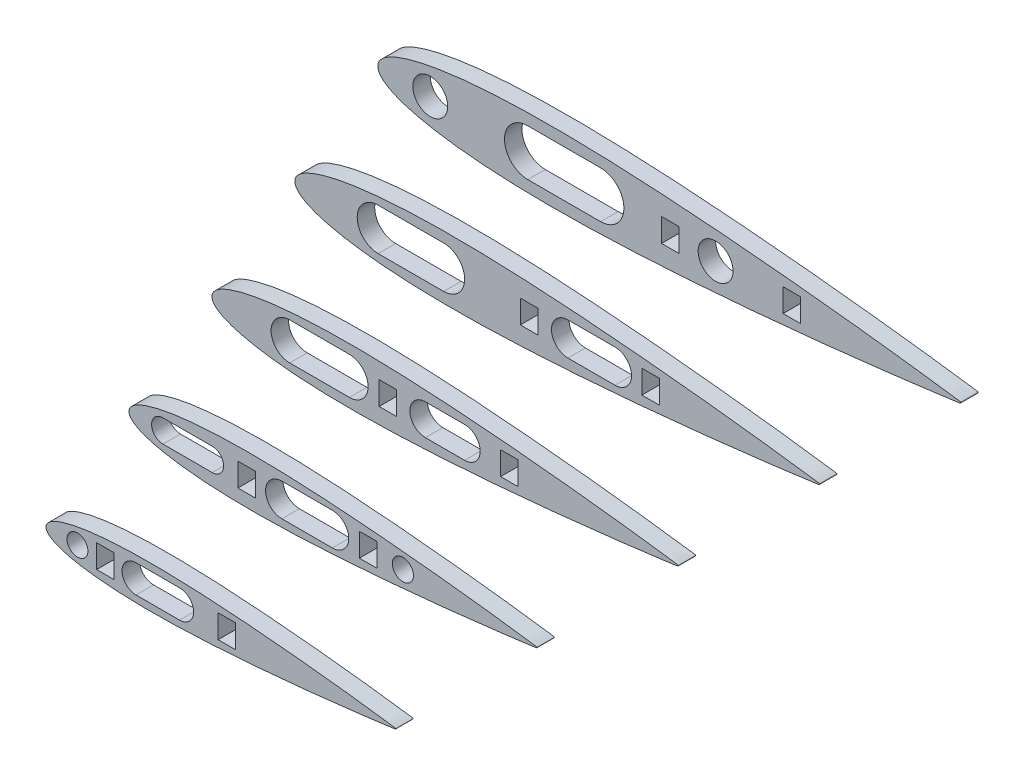
SolidWorks part; units mm, degrees
material "Balsa"
ref_plane "Front Plane" through (0, 0, 0) normal (1, 0, 0) x (0, 1, 0)
ref_plane "Top Plane" through (0, 0, 0) normal (0, 0, 1) x (0, 1, 0)
ref_plane "Right Plane" through (0, 0, 0) normal (0, 1, 0) x (-1, 0, 0)
curve "Curve1"
  spline degree 3 poles (0.0004, -0.0044, 0) (-0.0002, 0, 0) (0.0004, 0.0044, 0) (0.0023, 0.0087, 0) (0.0053, 0.0128, 0) (0.0094, 0.0167, 0) (0.0147, 0.0206, 0) (0.0211, 0.0243, 0) (0.0286, 0.0279, 0) (0.0372, 0.0313, 0) (0.0468, 0.0347, 0) (0.0576, 0.0378, 0) (0.0693, 0.0408, 0) (0.0821, 0.0436, 0) (0.0958, 0.0462, 0) (0.1104, 0.0486, 0) (0.126, 0.0507, 0) (0.1425, 0.0527, 0) (0.1597, 0.0544, 0) (0.1778, 0.056, 0) (0.1966, 0.0572, 0) (0.2162, 0.0583, 0) (0.2364, 0.0591, 0) (0.2572, 0.0596, 0) (0.2786, 0.06, 0) (0.3005, 0.0601, 0) (0.3228, 0.0599, 0) (0.3456, 0.0596, 0) (0.3688, 0.0591, 0) (0.3922, 0.0583, 0) (0.4159, 0.0574, 0) (0.4398, 0.0563, 0) (0.4638, 0.0551, 0) (0.4879, 0.0537, 0) (0.5121, 0.0522, 0) (0.5362, 0.0505, 0) (0.5602, 0.0488, 0) (0.5841, 0.0469, 0) (0.6078, 0.045, 0) (0.6313, 0.043, 0) (0.6544, 0.0409, 0) (0.6772, 0.0388, 0) (0.6995, 0.0367, 0) (0.7214, 0.0345, 0) (0.7428, 0.0324, 0) (0.7636, 0.0302, 0) (0.7838, 0.028, 0) (0.8033, 0.0259, 0) (0.8222, 0.0238, 0) (0.8402, 0.0217, 0) (0.8575, 0.0196, 0) (0.874, 0.0177, 0) (0.8895, 0.0158, 0) (0.9042, 0.014, 0) (0.9179, 0.0122, 0) (0.9307, 0.0106, 0) (0.9424, 0.0091, 0) (0.9531, 0.0077, 0) (0.9627, 0.0064, 0) (0.9713, 0.0052, 0) (0.9788, 0.0042, 0) (0.9851, 0.0033, 0) (0.9903, 0.0026, 0) (0.9944, 0.002, 0) (0.9973, 0.0017, 0) (0.999, 0.0013, 0) (1.0007, 0.0014, 0) (1.0007, -0.0014, 0) (0.999, -0.0013, 0) (0.9973, -0.0017, 0) (0.9944, -0.002, 0) (0.9903, -0.0026, 0) (0.9851, -0.0033, 0) (0.9788, -0.0042, 0) (0.9713, -0.0052, 0) (0.9627, -0.0064, 0) (0.9531, -0.0077, 0) (0.9424, -0.0091, 0) (0.9307, -0.0106, 0) (0.9179, -0.0122, 0) (0.9042, -0.014, 0) (0.8895, -0.0158, 0) (0.874, -0.0177, 0) (0.8575, -0.0196, 0) (0.8402, -0.0217, 0) (0.8222, -0.0238, 0) (0.8033, -0.0259, 0) (0.7838, -0.028, 0) (0.7636, -0.0302, 0) (0.7428, -0.0324, 0) (0.7214, -0.0345, 0) (0.6995, -0.0367, 0) (0.6772, -0.0388, 0) (0.6544, -0.0409, 0) (0.6313, -0.043, 0) (0.6078, -0.045, 0) (0.5841, -0.0469, 0) (0.5602, -0.0488, 0) (0.5362, -0.0505, 0) (0.5121, -0.0522, 0) (0.4879, -0.0537, 0) (0.4638, -0.0551, 0) (0.4398, -0.0563, 0) (0.4159, -0.0574, 0) (0.3922, -0.0583, 0) (0.3688, -0.0591, 0) (0.3456, -0.0596, 0) (0.3228, -0.0599, 0) (0.3005, -0.0601, 0) (0.2786, -0.06, 0) (0.2572, -0.0596, 0) (0.2364, -0.0591, 0) (0.2162, -0.0583, 0) (0.1966, -0.0572, 0) (0.1778, -0.056, 0) (0.1597, -0.0544, 0) (0.1425, -0.0527, 0) (0.126, -0.0507, 0) (0.1104, -0.0486, 0) (0.0958, -0.0462, 0) (0.0821, -0.0436, 0) (0.0693, -0.0408, 0) (0.0576, -0.0378, 0) (0.0468, -0.0347, 0) (0.0372, -0.0313, 0) (0.0286, -0.0279, 0) (0.0211, -0.0243, 0) (0.0147, -0.0206, 0) (0.0094, -0.0167, 0) (0.0053, -0.0128, 0) (0.0023, -0.0087, 0) (0.0004, -0.0044, 0) (-0.0002, 0, 0) (0.0004, 0.0044, 0) knots -0.006773 -0.004321 -0.002106 0 0.002106 0.004321 0.006773 0.009557 0.012734 0.016343 0.020406 0.024934 0.029933 0.035402 0.041337 0.047732 0.054575 0.061857 0.069565 0.077682 0.086195 0.095084 0.104333 0.113922 0.123829 0.134035 0.144516 0.155249 0.16621 0.177376 0.18872 0.200217 0.21184 0.223563 0.235359 0.2472 0.259058 0.270907 0.282718 0.294465 0.306118 0.317651 0.329037 0.340249 0.35126 0.362045 0.372579 0.382836 0.392793 0.402425 0.411711 0.420628 0.429156 0.437273 0.444962 0.452203 0.458979 0.465275 0.471075 0.476366 0.481134 0.485369 0.48906 0.492198 0.494776 0.496788 0.498228 0.499094 0.499383 0.500617 0.500906 0.501772 0.503212 0.505224 0.507802 0.51094 0.514631 0.518866 0.523634 0.528925 0.534725 0.541021 0.547797 0.555038 0.562727 0.570844 0.579372 0.588289 0.597575 0.607207 0.617164 0.627421 0.637955 0.64874 0.659751 0.670963 0.682349 0.693882 0.705535 0.717282 0.729093 0.740942 0.7528 0.764641 0.776437 0.78816 0.799783 0.81128 0.822624 0.83379 0.844751 0.855484 0.865965 0.876171 0.886078 0.895667 0.904916 0.913805 0.922318 0.930435 0.938143 0.945425 0.952268 0.958663 0.964598 0.970067 0.975066 0.979594 0.983657 0.987266 0.990443 0.993227 0.995679 0.997894 1 1.002106 1.004321 1.006773 periodic
sketch "Sketch1" plane through (0, 0, 0) normal (0, 0, 1) x (0, 1, 0)
  line L0 (0, 0) -> (0, -100.0545) construction
  line L13 (0, -38.25) -> (0, -25.75) construction
  line L14 (-4, -38.25) -> (-4, -25.75)
  line L15 (4, -38.25) -> (4, -25.75)
  arc A0 (-4, -38.25) -> (4, -38.25) centre (0, -38.25) ccw
  arc A1 (4, -25.75) -> (-4, -25.75) centre (0, -25.75) ccw
  circle A2 centre (0, -9) radius 3
  circle A3 centre (0, -58) radius 3
  spline S1 degree 3 poles (0.4387, -0.0412) (0, 0.0201) (-0.4387, -0.0412) (-0.8662, -0.226) (-1.2776, -0.528) (-1.6748, -0.9434) (-2.0591, -1.4711) (-2.4309, -2.1101) (-2.7897, -2.8597) (-3.1348, -3.7183) (-3.4651, -4.6844) (-3.7795, -5.7559) (-4.0769, -6.9304) (-4.3561, -8.2052) (-4.616, -9.5775) (-4.8557, -11.044) (-5.0742, -12.6015) (-5.2707, -14.2462) (-5.4445, -15.9743) (-5.5952, -17.7819) (-5.7224, -19.6647) (-5.8259, -21.6183) (-5.9057, -23.6381) (-5.962, -25.7195) (-5.9951, -27.8576) (-6.0054, -30.0473) (-5.9936, -32.2837) (-5.9605, -34.5614) (-5.907, -36.8751) (-5.8341, -39.2195) (-5.7428, -41.589) (-5.6343, -43.9782) (-5.5099, -46.3815) (-5.3708, -48.7932) (-5.2183, -51.2076) (-5.0537, -53.6193) (-4.8783, -56.0225) (-4.6934, -58.4117) (-4.5002, -60.7812) (-4.3, -63.1255) (-4.0941, -65.4392) (-3.8836, -67.7168) (-3.6696, -69.953) (-3.4533, -72.1426) (-3.2359, -74.2806) (-3.0182, -76.3618) (-2.8015, -78.3814) (-2.5868, -80.3348) (-2.375, -82.2173) (-2.1672, -84.0245) (-1.9644, -85.7523) (-1.7676, -87.3966) (-1.5778, -88.9536) (-1.3958, -90.4195) (-1.2228, -91.7911) (-1.0595, -93.0651) (-0.907, -94.2385) (-0.766, -95.3085) (-0.6374, -96.2728) (-0.522, -97.1289) (-0.4205, -97.8751) (-0.333, -98.5092) (-0.2622, -99.0307) (-0.2026, -99.4358) (-0.1688, -99.7301) (-0.1323, -99.8992) (-0.1356, -100.0726) (0.1356, -100.0726) (0.1323, -99.8992) (0.1688, -99.7301) (0.2026, -99.4358) (0.2622, -99.0307) (0.333, -98.5092) (0.4205, -97.8751) (0.522, -97.1289) (0.6374, -96.2728) (0.766, -95.3085) (0.907, -94.2385) (1.0595, -93.0651) (1.2228, -91.7911) (1.3958, -90.4195) (1.5778, -88.9536) (1.7676, -87.3966) (1.9644, -85.7523) (2.1672, -84.0245) (2.375, -82.2173) (2.5868, -80.3348) (2.8015, -78.3814) (3.0182, -76.3618) (3.2359, -74.2806) (3.4533, -72.1426) (3.6696, -69.953) (3.8836, -67.7168) (4.0941, -65.4392) (4.3, -63.1255) (4.5002, -60.7812) (4.6934, -58.4117) (4.8783, -56.0225) (5.0537, -53.6193) (5.2183, -51.2076) (5.3708, -48.7932) (5.5099, -46.3815) (5.6343, -43.9782) (5.7428, -41.589) (5.8341, -39.2195) (5.907, -36.8751) (5.9605, -34.5614) (5.9936, -32.2837) (6.0054, -30.0473) (5.9951, -27.8576) (5.962, -25.7195) (5.9057, -23.6381) (5.8259, -21.6183) (5.7224, -19.6647) (5.5952, -17.7819) (5.4445, -15.9743) (5.2707, -14.2462) (5.0742, -12.6015) (4.8557, -11.044) (4.616, -9.5775) (4.3561, -8.2052) (4.0769, -6.9304) (3.7795, -5.7559) (3.4651, -4.6844) (3.1348, -3.7183) (2.7897, -2.8597) (2.4309, -2.1101) (2.0591, -1.4711) (1.6748, -0.9434) (1.2776, -0.528) (0.8662, -0.226) (0.4387, -0.0412) (0, 0.0201) (-0.4387, -0.0412) knots -0.006773 -0.004321 -0.002106 0 0.002106 0.004321 0.006773 0.009557 0.012734 0.016343 0.020406 0.024934 0.029933 0.035402 0.041337 0.047732 0.054575 0.061857 0.069565 0.077682 0.086195 0.095084 0.104333 0.113922 0.123829 0.134035 0.144516 0.155249 0.16621 0.177376 0.18872 0.200217 0.21184 0.223563 0.235359 0.2472 0.259058 0.270907 0.282718 0.294465 0.306118 0.317651 0.329037 0.340249 0.35126 0.362045 0.372579 0.382836 0.392793 0.402425 0.411711 0.420628 0.429156 0.437273 0.444962 0.452203 0.458979 0.465275 0.471075 0.476366 0.481134 0.485369 0.48906 0.492198 0.494776 0.496788 0.498228 0.499094 0.499383 0.500617 0.500906 0.501772 0.503212 0.505224 0.507802 0.51094 0.514631 0.518866 0.523634 0.528925 0.534725 0.541021 0.547797 0.555038 0.562727 0.570844 0.579372 0.588289 0.597575 0.607207 0.617164 0.627421 0.637955 0.64874 0.659751 0.670963 0.682349 0.693882 0.705535 0.717282 0.729093 0.740942 0.7528 0.764641 0.776437 0.78816 0.799783 0.81128 0.822624 0.83379 0.844751 0.855484 0.865965 0.876171 0.886078 0.895667 0.904916 0.913805 0.922318 0.930435 0.938143 0.945425 0.952268 0.958663 0.964598 0.970067 0.975066 0.979594 0.983657 0.987266 0.990443 0.993227 0.995679 0.997894 1 1.002106 1.004321 1.006773 only from (0, 0) to (0, 0)
  point P14 (0, -32)
  dimension "D7" = 4
  dimension "D11" = 6
  dimension "D12" = 6
  dimension "D1" = 100.0545
  dimension "D2" = 26
  dimension "D3" = 23
  dimension "D4" = 9
  dimension "D9" = 12.5
ref_plane "Plane2" through (0, 0, 100) normal (0, 0, 1) x (0, 1, 0)
extrude "Boss-Extrude2" add sketch "Sketch1" along normal blind 3
pattern_linear "LPattern2" count 5 spacing 24.25 along (0, 0, -1)
ref_plane "Plane3" through (0, 0, 24.25) normal (0, 0, 1) x (0, 1, 0)
ref_plane "Plane4" through (0, 0, 48.5) normal (0, 0, 1) x (0, 1, 0)
ref_plane "Plane5" through (0, 0, 72.75) normal (0, 0, 1) x (0, 1, 0)
ref_plane "Plane6" through (0, 0, 97) normal (0, 0, 1) x (0, 1, 0)
sketch "Sketch3" plane through (0, 0, 24.25) normal (0, 0, 1) x (0, 1, 0)
  line L0 (0, -10.0054) -> (0, -100.0545) construction
  line L1 (0, -56.9058) -> (0, -64.9781) construction
  line L2 (2.8402, -56.9058) -> (2.8402, -64.9781)
  line L3 (-2.8402, -56.9058) -> (-2.8402, -64.9781)
  line L20 (3.6, -35.5585) -> (3.6, -24.3085)
  line L21 (-3.6, -24.3085) -> (-3.6, -35.5585)
  arc A0 (2.8402, -56.9058) -> (-2.8402, -56.9058) centre (0, -56.9058) ccw
  arc A1 (-2.8402, -64.9781) -> (2.8402, -64.9781) centre (0, -64.9781) ccw
  arc A8 (3.6, -24.3085) -> (-3.6, -24.3085) centre (0, -24.3085) ccw
  arc A9 (-3.6, -35.5585) -> (3.6, -35.5585) centre (0, -35.5585) ccw
  spline S2 degree 3 poles (0.3948, -10.0425) (0, -9.9874) (-0.3948, -10.0425) (-0.7796, -10.2088) (-1.1499, -10.4806) (-1.5073, -10.8545) (-1.8532, -11.3294) (-2.1878, -11.9046) (-2.5107, -12.5792) (-2.8213, -13.3519) (-3.1186, -14.2214) (-3.4016, -15.1857) (-3.6692, -16.2428) (-3.9205, -17.3901) (-4.1544, -18.6252) (-4.3702, -19.9451) (-4.5668, -21.3468) (-4.7436, -22.827) (-4.9001, -24.3823) (-5.0357, -26.0092) (-5.1502, -27.7036) (-5.2433, -29.4619) (-5.3152, -31.2797) (-5.3658, -33.153) (-5.3956, -35.0772) (-5.4049, -37.048) (-5.3943, -39.0607) (-5.3645, -41.1107) (-5.3163, -43.193) (-5.2507, -45.303) (-5.1685, -47.4356) (-5.0709, -49.5859) (-4.9589, -51.7488) (-4.8337, -53.9193) (-4.6965, -56.0923) (-4.5483, -58.2628) (-4.3904, -60.4257) (-4.224, -62.576) (-4.0502, -64.7085) (-3.87, -66.8184) (-3.6847, -68.9007) (-3.4952, -70.9506) (-3.3027, -72.9632) (-3.108, -74.9338) (-2.9123, -76.858) (-2.7164, -78.731) (-2.5214, -80.5487) (-2.3281, -82.3067) (-2.1375, -84.001) (-1.9505, -85.6275) (-1.768, -87.1825) (-1.5909, -88.6624) (-1.42, -90.0637) (-1.2563, -91.383) (-1.1005, -92.6174) (-0.9536, -93.764) (-0.8163, -94.8201) (-0.6894, -95.7831) (-0.5737, -96.6509) (-0.4698, -97.4215) (-0.3785, -98.093) (-0.2997, -98.6637) (-0.2359, -99.1331) (-0.1824, -99.4976) (-0.152, -99.7625) (-0.119, -99.9147) (-0.122, -100.0708) (0.122, -100.0708) (0.119, -99.9147) (0.152, -99.7625) (0.1824, -99.4976) (0.2359, -99.1331) (0.2997, -98.6637) (0.3785, -98.093) (0.4698, -97.4215) (0.5737, -96.6509) (0.6894, -95.7831) (0.8163, -94.8201) (0.9536, -93.764) (1.1005, -92.6174) (1.2563, -91.383) (1.42, -90.0637) (1.5909, -88.6624) (1.768, -87.1825) (1.9505, -85.6275) (2.1375, -84.001) (2.3281, -82.3067) (2.5214, -80.5487) (2.7164, -78.731) (2.9123, -76.858) (3.108, -74.9338) (3.3027, -72.9632) (3.4952, -70.9506) (3.6847, -68.9007) (3.87, -66.8184) (4.0502, -64.7085) (4.224, -62.576) (4.3904, -60.4257) (4.5483, -58.2628) (4.6965, -56.0923) (4.8337, -53.9193) (4.9589, -51.7488) (5.0709, -49.5859) (5.1685, -47.4356) (5.2507, -45.303) (5.3163, -43.193) (5.3645, -41.1107) (5.3943, -39.0607) (5.4049, -37.048) (5.3956, -35.0772) (5.3658, -33.153) (5.3152, -31.2797) (5.2433, -29.4619) (5.1502, -27.7036) (5.0357, -26.0092) (4.9001, -24.3823) (4.7436, -22.827) (4.5668, -21.3468) (4.3702, -19.9451) (4.1544, -18.6252) (3.9205, -17.3901) (3.6692, -16.2428) (3.4016, -15.1857) (3.1186, -14.2214) (2.8213, -13.3519) (2.5107, -12.5792) (2.1878, -11.9046) (1.8532, -11.3294) (1.5073, -10.8545) (1.1499, -10.4806) (0.7796, -10.2088) (0.3948, -10.0425) (0, -9.9874) (-0.3948, -10.0425) knots -0.006773 -0.004321 -0.002106 0 0.002106 0.004321 0.006773 0.009557 0.012734 0.016343 0.020406 0.024934 0.029933 0.035402 0.041337 0.047732 0.054575 0.061857 0.069565 0.077682 0.086195 0.095084 0.104333 0.113922 0.123829 0.134035 0.144516 0.155249 0.16621 0.177376 0.18872 0.200217 0.21184 0.223563 0.235359 0.2472 0.259058 0.270907 0.282718 0.294465 0.306118 0.317651 0.329037 0.340249 0.35126 0.362045 0.372579 0.382836 0.392793 0.402425 0.411711 0.420628 0.429156 0.437273 0.444962 0.452203 0.458979 0.465275 0.471075 0.476366 0.481134 0.485369 0.48906 0.492198 0.494776 0.496788 0.498228 0.499094 0.499383 0.500617 0.500906 0.501772 0.503212 0.505224 0.507802 0.51094 0.514631 0.518866 0.523634 0.528925 0.534725 0.541021 0.547797 0.555038 0.562727 0.570844 0.579372 0.588289 0.597575 0.607207 0.617164 0.627421 0.637955 0.64874 0.659751 0.670963 0.682349 0.693882 0.705535 0.717282 0.729093 0.740942 0.7528 0.764641 0.776437 0.78816 0.799783 0.81128 0.822624 0.83379 0.844751 0.855484 0.865965 0.876171 0.886078 0.895667 0.904916 0.913805 0.922318 0.930435 0.938143 0.945425 0.952268 0.958663 0.964598 0.970067 0.975066 0.979594 0.983657 0.987266 0.990443 0.993227 0.995679 0.997894 1 1.002106 1.004321 1.006773 only from (0, -10.0054) to (0, -10.0054)
  point P3 (0, -60.9419)
sketch "Sketch4" plane through (0, 0, 48.5) normal (0, 0, 1) x (0, 1, 0)
  line L0 (0, -20.0109) -> (0.0006, -100.0545) construction
  line L1 (0.0003, -63.4032) -> (0.0003, -56.6622) construction
  line L2 (-2.6642, -63.4032) -> (-2.6643, -56.6622)
  line L3 (2.6649, -63.4031) -> (2.6648, -56.6622)
  line L20 (3.2001, -43.6288) -> (3.2001, -33.3726)
  line L21 (-3.1999, -33.3726) -> (-3.1999, -43.6288)
  arc A0 (-2.6642, -63.4032) -> (2.6649, -63.4031) centre (0.0003, -63.4032) ccw
  arc A1 (2.6648, -56.6622) -> (-2.6643, -56.6622) centre (0.0003, -56.6622) ccw
  arc A8 (3.2001, -33.3726) -> (-3.1999, -33.3726) centre (0.0001, -33.3726) ccw
  arc A9 (-3.1999, -43.6288) -> (3.2001, -43.6288) centre (0.0001, -43.6288) ccw
  spline S0 degree 3 poles (0.4387, -0.0412) (0, 0.0201) (-0.4387, -0.0412) (-0.8662, -0.226) (-1.2776, -0.528) (-1.6748, -0.9434) (-2.0591, -1.4711) (-2.4309, -2.1101) (-2.7897, -2.8597) (-3.1348, -3.7183) (-3.4651, -4.6844) (-3.7795, -5.7559) (-4.0769, -6.9304) (-4.3561, -8.2052) (-4.616, -9.5775) (-4.8557, -11.044) (-5.0742, -12.6015) (-5.2707, -14.2462) (-5.4445, -15.9743) (-5.5952, -17.7819) (-5.7224, -19.6647) (-5.8259, -21.6183) (-5.9057, -23.6381) (-5.962, -25.7195) (-5.9951, -27.8576) (-6.0054, -30.0473) (-5.9936, -32.2837) (-5.9605, -34.5614) (-5.907, -36.8751) (-5.8341, -39.2195) (-5.7428, -41.589) (-5.6343, -43.9782) (-5.5099, -46.3815) (-5.3708, -48.7932) (-5.2183, -51.2076) (-5.0537, -53.6193) (-4.8783, -56.0225) (-4.6934, -58.4117) (-4.5002, -60.7812) (-4.3, -63.1255) (-4.0941, -65.4392) (-3.8836, -67.7168) (-3.6696, -69.953) (-3.4533, -72.1426) (-3.2359, -74.2806) (-3.0182, -76.3618) (-2.8015, -78.3814) (-2.5868, -80.3348) (-2.375, -82.2173) (-2.1672, -84.0245) (-1.9644, -85.7523) (-1.7676, -87.3966) (-1.5778, -88.9536) (-1.3958, -90.4195) (-1.2228, -91.7911) (-1.0595, -93.0651) (-0.907, -94.2385) (-0.766, -95.3085) (-0.6374, -96.2728) (-0.522, -97.1289) (-0.4205, -97.8751) (-0.333, -98.5092) (-0.2622, -99.0307) (-0.2026, -99.4358) (-0.1688, -99.7301) (-0.1323, -99.8992) (-0.1356, -100.0726) (0.1356, -100.0726) (0.1323, -99.8992) (0.1688, -99.7301) (0.2026, -99.4358) (0.2622, -99.0307) (0.333, -98.5092) (0.4205, -97.8751) (0.522, -97.1289) (0.6374, -96.2728) (0.766, -95.3085) (0.907, -94.2385) (1.0595, -93.0651) (1.2228, -91.7911) (1.3958, -90.4195) (1.5778, -88.9536) (1.7676, -87.3966) (1.9644, -85.7523) (2.1672, -84.0245) (2.375, -82.2173) (2.5868, -80.3348) (2.8015, -78.3814) (3.0182, -76.3618) (3.2359, -74.2806) (3.4533, -72.1426) (3.6696, -69.953) (3.8836, -67.7168) (4.0941, -65.4392) (4.3, -63.1255) (4.5002, -60.7812) (4.6934, -58.4117) (4.8783, -56.0225) (5.0537, -53.6193) (5.2183, -51.2076) (5.3708, -48.7932) (5.5099, -46.3815) (5.6343, -43.9782) (5.7428, -41.589) (5.8341, -39.2195) (5.907, -36.8751) (5.9605, -34.5614) (5.9936, -32.2837) (6.0054, -30.0473) (5.9951, -27.8576) (5.962, -25.7195) (5.9057, -23.6381) (5.8259, -21.6183) (5.7224, -19.6647) (5.5952, -17.7819) (5.4445, -15.9743) (5.2707, -14.2462) (5.0742, -12.6015) (4.8557, -11.044) (4.616, -9.5775) (4.3561, -8.2052) (4.0769, -6.9304) (3.7795, -5.7559) (3.4651, -4.6844) (3.1348, -3.7183) (2.7897, -2.8597) (2.4309, -2.1101) (2.0591, -1.4711) (1.6748, -0.9434) (1.2776, -0.528) (0.8662, -0.226) (0.4387, -0.0412) (0, 0.0201) (-0.4387, -0.0412) knots -0.006773 -0.004321 -0.002106 0 0.002106 0.004321 0.006773 0.009557 0.012734 0.016343 0.020406 0.024934 0.029933 0.035402 0.041337 0.047732 0.054575 0.061857 0.069565 0.077682 0.086195 0.095084 0.104333 0.113922 0.123829 0.134035 0.144516 0.155249 0.16621 0.177376 0.18872 0.200217 0.21184 0.223563 0.235359 0.2472 0.259058 0.270907 0.282718 0.294465 0.306118 0.317651 0.329037 0.340249 0.35126 0.362045 0.372579 0.382836 0.392793 0.402425 0.411711 0.420628 0.429156 0.437273 0.444962 0.452203 0.458979 0.465275 0.471075 0.476366 0.481134 0.485369 0.48906 0.492198 0.494776 0.496788 0.498228 0.499094 0.499383 0.500617 0.500906 0.501772 0.503212 0.505224 0.507802 0.51094 0.514631 0.518866 0.523634 0.528925 0.534725 0.541021 0.547797 0.555038 0.562727 0.570844 0.579372 0.588289 0.597575 0.607207 0.617164 0.627421 0.637955 0.64874 0.659751 0.670963 0.682349 0.693882 0.705535 0.717282 0.729093 0.740942 0.7528 0.764641 0.776437 0.78816 0.799783 0.81128 0.822624 0.83379 0.844751 0.855484 0.865965 0.876171 0.886078 0.895667 0.904916 0.913805 0.922318 0.930435 0.938143 0.945425 0.952268 0.958663 0.964598 0.970067 0.975066 0.979594 0.983657 0.987266 0.990443 0.993227 0.995679 0.997894 1 1.002106 1.004321 1.006773 only from (0, 0) to (0, 0) construction
  spline S2 degree 3 poles (0.351, -20.0439) (0, -19.9948) (-0.351, -20.0439) (-0.693, -20.1917) (-1.0221, -20.4333) (-1.3398, -20.7656) (-1.6473, -21.1878) (-1.9447, -21.699) (-2.2318, -22.2986) (-2.5078, -22.9856) (-2.7721, -23.7584) (-3.0236, -24.6156) (-3.2615, -25.5552) (-3.4849, -26.575) (-3.6928, -27.6729) (-3.8846, -28.8461) (-4.0594, -30.0921) (-4.2166, -31.4078) (-4.3556, -32.7903) (-4.4762, -34.2364) (-4.578, -35.7426) (-4.6608, -37.3055) (-4.7246, -38.9214) (-4.7696, -40.5865) (-4.7961, -42.2969) (-4.8044, -44.0487) (-4.7949, -45.8378) (-4.7685, -47.66) (-4.7256, -49.511) (-4.6673, -51.3865) (-4.5943, -53.2821) (-4.5075, -55.1935) (-4.408, -57.1161) (-4.2967, -59.0454) (-4.1747, -60.977) (-4.043, -62.9063) (-3.9027, -64.8289) (-3.7548, -66.7402) (-3.6002, -68.6358) (-3.4401, -70.5113) (-3.2754, -72.3622) (-3.1069, -74.1843) (-2.9358, -75.9733) (-2.7628, -77.725) (-2.5888, -79.4353) (-2.4147, -81.1003) (-2.2413, -82.716) (-2.0695, -84.2787) (-1.9001, -85.7847) (-1.7339, -87.2305) (-1.5716, -88.6128) (-1.4142, -89.9282) (-1.2623, -91.1737) (-1.1168, -92.3465) (-0.9783, -93.4438) (-0.8477, -94.463) (-0.7257, -95.4017) (-0.6129, -96.2577) (-0.5101, -97.0291) (-0.4177, -97.714) (-0.3365, -98.311) (-0.2665, -98.8182) (-0.2098, -99.2355) (-0.1622, -99.5595) (-0.1352, -99.795) (-0.1059, -99.9302) (-0.1086, -100.069) (0.1084, -100.069) (0.1057, -99.9302) (0.135, -99.795) (0.162, -99.5595) (0.2096, -99.2355) (0.2663, -98.8182) (0.3363, -98.311) (0.4175, -97.714) (0.5098, -97.0291) (0.6127, -96.2577) (0.7255, -95.4017) (0.8475, -94.463) (0.9781, -93.4438) (1.1166, -92.3465) (1.2621, -91.1737) (1.414, -89.9282) (1.5715, -88.6128) (1.7337, -87.2305) (1.8999, -85.7847) (2.0693, -84.2787) (2.2411, -82.716) (2.4145, -81.1003) (2.5886, -79.4353) (2.7626, -77.725) (2.9356, -75.9733) (3.1068, -74.1843) (3.2752, -72.3622) (3.44, -70.5113) (3.6001, -68.6359) (3.7546, -66.7402) (3.9026, -64.8289) (4.0429, -62.9064) (4.1746, -60.977) (4.2966, -59.0454) (4.4079, -57.1161) (4.5074, -55.1935) (4.5942, -53.2821) (4.6672, -51.3865) (4.7256, -49.511) (4.7684, -47.66) (4.7949, -45.8378) (4.8043, -44.0488) (4.796, -42.2969) (4.7696, -40.5865) (4.7246, -38.9214) (4.6607, -37.3055) (4.5779, -35.7426) (4.4762, -34.2364) (4.3556, -32.7904) (4.2165, -31.4078) (4.0593, -30.0921) (3.8846, -28.8461) (3.6928, -27.6729) (3.4849, -26.5751) (3.2615, -25.5552) (3.0236, -24.6156) (2.7721, -23.7584) (2.5078, -22.9856) (2.2318, -22.2986) (1.9447, -21.699) (1.6473, -21.1878) (1.3398, -20.7656) (1.0221, -20.4333) (0.693, -20.1917) (0.351, -20.0439) (0, -19.9948) (-0.351, -20.0439) knots -0.006773 -0.004321 -0.002106 0 0.002106 0.004321 0.006773 0.009557 0.012734 0.016343 0.020406 0.024934 0.029933 0.035402 0.041337 0.047732 0.054575 0.061857 0.069565 0.077682 0.086195 0.095084 0.104333 0.113922 0.123829 0.134035 0.144516 0.155249 0.16621 0.177376 0.18872 0.200217 0.21184 0.223563 0.235359 0.2472 0.259058 0.270907 0.282718 0.294465 0.306118 0.317651 0.329037 0.340249 0.35126 0.362045 0.372579 0.382836 0.392793 0.402425 0.411711 0.420628 0.429156 0.437273 0.444962 0.452203 0.458979 0.465275 0.471075 0.476366 0.481134 0.485369 0.48906 0.492198 0.494776 0.496788 0.498228 0.499094 0.499383 0.500617 0.500906 0.501772 0.503212 0.505224 0.507802 0.51094 0.514631 0.518866 0.523634 0.528925 0.534725 0.541021 0.547797 0.555038 0.562727 0.570844 0.579372 0.588289 0.597575 0.607207 0.617164 0.627421 0.637955 0.64874 0.659751 0.670963 0.682349 0.693882 0.705535 0.717282 0.729093 0.740942 0.7528 0.764641 0.776437 0.78816 0.799783 0.81128 0.822624 0.83379 0.844751 0.855484 0.865965 0.876171 0.886078 0.895667 0.904916 0.913805 0.922318 0.930435 0.938143 0.945425 0.952268 0.958663 0.964598 0.970067 0.975066 0.979594 0.983657 0.987266 0.990443 0.993227 0.995679 0.997894 1 1.002106 1.004321 1.006773 only from (0, -20.0109) to (0, -20.0109)
  point P4 (0.0003, -60.0327)
sketch "Sketch5" plane through (0, 0, 72.75) normal (0, 0, 1) x (0, 1, 0)
  line L0 (0.0495, -30.0163) -> (0.0495, -100.0116) construction
  line L1 (0.0495, -44.328) -> (0.0495, -35.8507) construction
  line L2 (-1.9011, -44.328) -> (-1.9011, -35.8507)
  line L3 (2, -44.328) -> (2, -35.8507)
  line L20 (2.8008, -64.9545) -> (2.8008, -56.2741)
  line L21 (-2.7992, -56.2741) -> (-2.7992, -64.9545)
  arc A0 (-1.9011, -44.328) -> (2, -44.328) centre (0.0495, -44.328) ccw
  arc A1 (2, -35.8507) -> (-1.9011, -35.8507) centre (0.0495, -35.8507) ccw
  circle A2 centre (0.0495, -77.056) radius 1.8186
  arc A8 (2.8008, -56.2741) -> (-2.7992, -56.2741) centre (0.0008, -56.2741) ccw
  arc A9 (-2.7992, -64.9545) -> (2.8008, -64.9545) centre (0.0008, -64.9545) ccw
  spline S2 degree 3 poles (0.3565, -30.0456) (0.0495, -30.0023) (-0.2576, -30.0448) (-0.5571, -30.1738) (-0.8453, -30.3848) (-1.1237, -30.6752) (-1.3932, -31.0442) (-1.654, -31.4913) (-1.9059, -32.0156) (-2.1482, -32.6163) (-2.3803, -33.2923) (-2.6014, -34.0421) (-2.8106, -34.8639) (-3.0072, -35.7561) (-3.1904, -36.7164) (-3.3595, -37.7428) (-3.5138, -38.8328) (-3.6528, -39.9839) (-3.7761, -41.1935) (-3.8832, -42.4586) (-3.9739, -43.7764) (-4.0482, -45.1439) (-4.1058, -46.5577) (-4.1471, -48.0146) (-4.1722, -49.5112) (-4.1814, -51.0441) (-4.1751, -52.6095) (-4.154, -54.2039) (-4.1186, -55.8236) (-4.0697, -57.4647) (-4.0079, -59.1235) (-3.9342, -60.796) (-3.8492, -62.4784) (-3.754, -64.1667) (-3.6495, -65.857) (-3.5364, -67.5453) (-3.4158, -69.2277) (-3.2885, -70.9003) (-3.1554, -72.5591) (-3.0174, -74.2003) (-2.8754, -75.8201) (-2.73, -77.4146) (-2.5823, -78.9801) (-2.4329, -80.5131) (-2.2825, -82.0098) (-2.1321, -83.4669) (-1.9822, -84.8808) (-1.8337, -86.2483) (-1.6871, -87.5663) (-1.5433, -88.8316) (-1.4029, -90.0412) (-1.2666, -91.1924) (-1.1351, -92.2824) (-1.0091, -93.3088) (-0.8892, -94.269) (-0.7761, -95.1609) (-0.6703, -95.9824) (-0.5726, -96.7316) (-0.4835, -97.4067) (-0.4034, -98.0061) (-0.3331, -98.5285) (-0.2724, -98.9725) (-0.2233, -99.3376) (-0.1819, -99.6212) (-0.1586, -99.8273) (-0.1331, -99.9456) (-0.1356, -100.067) (0.0542, -100.0673) (0.0521, -99.9459) (0.0778, -99.8276) (0.1017, -99.6216) (0.1438, -99.3381) (0.1938, -98.9731) (0.2557, -98.5293) (0.3273, -98.007) (0.4089, -97.4078) (0.4998, -96.733) (0.5995, -95.9841) (0.7073, -95.1628) (0.8227, -94.2712) (0.9451, -93.3113) (1.0738, -92.2853) (1.2081, -91.1956) (1.3473, -90.0447) (1.4908, -88.8355) (1.6379, -87.5706) (1.7879, -86.253) (1.9399, -84.8858) (2.0934, -83.4723) (2.2477, -82.0156) (2.4018, -80.5193) (2.5552, -78.9868) (2.707, -77.4216) (2.8564, -75.8274) (3.0026, -74.2081) (3.1449, -72.5672) (3.2822, -70.9087) (3.4138, -69.2365) (3.5387, -67.5544) (3.6561, -65.8664) (3.7651, -64.1764) (3.8646, -62.4883) (3.9539, -60.8062) (4.0319, -59.1338) (4.098, -57.4752) (4.1512, -55.8342) (4.1907, -54.2147) (4.2159, -52.6203) (4.2262, -51.0549) (4.2209, -49.522) (4.1997, -48.0253) (4.1622, -46.5683) (4.1082, -45.1544) (4.0375, -43.7868) (3.9501, -42.4687) (3.8463, -41.2033) (3.7261, -39.9934) (3.5901, -38.8419) (3.4385, -37.7515) (3.2721, -36.7247) (3.0914, -35.7639) (2.8971, -34.8713) (2.69, -34.0489) (2.4708, -33.2986) (2.2405, -32.622) (1.9997, -32.0206) (1.7492, -31.4956) (1.4895, -31.048) (1.221, -30.6783) (0.9433, -30.3871) (0.6556, -30.1753) (0.3565, -30.0456) (0.0495, -30.0023) (-0.2576, -30.0448) knots -0.006773 -0.004321 -0.002106 0 0.002106 0.004321 0.006773 0.009557 0.012734 0.016343 0.020406 0.024934 0.029933 0.035402 0.041337 0.047732 0.054575 0.061857 0.069565 0.077682 0.086195 0.095084 0.104333 0.113922 0.123829 0.134035 0.144516 0.155249 0.16621 0.177376 0.18872 0.200217 0.21184 0.223563 0.235359 0.2472 0.259058 0.270907 0.282718 0.294465 0.306118 0.317651 0.329037 0.340249 0.35126 0.362045 0.372579 0.382836 0.392793 0.402425 0.411711 0.420628 0.429156 0.437273 0.444962 0.452203 0.458979 0.465275 0.471075 0.476366 0.481134 0.485369 0.48906 0.492198 0.494776 0.496788 0.498228 0.499094 0.499383 0.500617 0.500906 0.501772 0.503212 0.505224 0.507802 0.51094 0.514631 0.518866 0.523634 0.528925 0.534725 0.541021 0.547797 0.555038 0.562727 0.570844 0.579372 0.588289 0.597575 0.607207 0.617164 0.627421 0.637955 0.64874 0.659751 0.670963 0.682349 0.693882 0.705535 0.717282 0.729093 0.740942 0.7528 0.764641 0.776437 0.78816 0.799783 0.81128 0.822624 0.83379 0.844751 0.855484 0.865965 0.876171 0.886078 0.895667 0.904916 0.913805 0.922318 0.930435 0.938143 0.945425 0.952268 0.958663 0.964598 0.970067 0.975066 0.979594 0.983657 0.987266 0.990443 0.993227 0.995679 0.997894 1 1.002106 1.004321 1.006773 only from (0.0495, -30.0163) to (0.0495, -30.0163)
  point P3 (0.0495, -40.0894)
sketch "Sketch6" plane through (0, 0, 97) normal (0, 0, 1) x (0, 1, 0)
  line L0 (0, 0) -> (-0.0015, -100.0545) construction
  line L8 (-2.001, -72.5844) -> (1.999, -72.5844)
  line L9 (1.999, -72.5844) -> (1.999, -69.5844)
  line L10 (1.999, -69.5844) -> (-2.001, -69.5844)
  line L11 (-2.001, -69.5844) -> (-2.001, -72.5844)
  line L16 (-2.0007, -51.7218) -> (1.9993, -51.7218)
  line L17 (1.9993, -51.7218) -> (1.9993, -48.7218)
  line L18 (1.9993, -48.7218) -> (-2.0007, -48.7218)
  line L19 (-2.0007, -48.7218) -> (-2.0007, -51.7218)
  line L20 (2.4, -62.9718) -> (2.4, -55.4718)
  line L21 (-2.4, -55.4718) -> (-2.4, -62.9718)
  circle A4 centre (0, -45.4218) radius 1.8
  arc A8 (2.4, -55.4718) -> (-2.4, -55.4718) centre (0, -55.4718) ccw
  arc A9 (-2.4, -62.9718) -> (2.4, -62.9718) centre (0, -62.9718) ccw
  spline S0 degree 3 poles (0.4387, -0.0412) (0, 0.0201) (-0.4387, -0.0412) (-0.8662, -0.226) (-1.2776, -0.528) (-1.6748, -0.9434) (-2.0591, -1.4711) (-2.4309, -2.1101) (-2.7897, -2.8597) (-3.1348, -3.7183) (-3.4651, -4.6844) (-3.7795, -5.7559) (-4.0769, -6.9304) (-4.3561, -8.2052) (-4.616, -9.5775) (-4.8557, -11.044) (-5.0742, -12.6015) (-5.2707, -14.2462) (-5.4445, -15.9743) (-5.5952, -17.7819) (-5.7224, -19.6647) (-5.8259, -21.6183) (-5.9057, -23.6381) (-5.962, -25.7195) (-5.9951, -27.8576) (-6.0054, -30.0473) (-5.9936, -32.2837) (-5.9605, -34.5614) (-5.907, -36.8751) (-5.8341, -39.2195) (-5.7428, -41.589) (-5.6343, -43.9782) (-5.5099, -46.3815) (-5.3708, -48.7932) (-5.2183, -51.2076) (-5.0537, -53.6193) (-4.8783, -56.0225) (-4.6934, -58.4117) (-4.5002, -60.7812) (-4.3, -63.1255) (-4.0941, -65.4392) (-3.8836, -67.7168) (-3.6696, -69.953) (-3.4533, -72.1426) (-3.2359, -74.2806) (-3.0182, -76.3618) (-2.8015, -78.3814) (-2.5868, -80.3348) (-2.375, -82.2173) (-2.1672, -84.0245) (-1.9644, -85.7523) (-1.7676, -87.3966) (-1.5778, -88.9536) (-1.3958, -90.4195) (-1.2228, -91.7911) (-1.0595, -93.0651) (-0.907, -94.2385) (-0.766, -95.3085) (-0.6374, -96.2728) (-0.522, -97.1289) (-0.4205, -97.8751) (-0.333, -98.5092) (-0.2622, -99.0307) (-0.2026, -99.4358) (-0.1688, -99.7301) (-0.1323, -99.8992) (-0.1356, -100.0726) (0.1356, -100.0726) (0.1323, -99.8992) (0.1688, -99.7301) (0.2026, -99.4358) (0.2622, -99.0307) (0.333, -98.5092) (0.4205, -97.8751) (0.522, -97.1289) (0.6374, -96.2728) (0.766, -95.3085) (0.907, -94.2385) (1.0595, -93.0651) (1.2228, -91.7911) (1.3958, -90.4195) (1.5778, -88.9536) (1.7676, -87.3966) (1.9644, -85.7523) (2.1672, -84.0245) (2.375, -82.2173) (2.5868, -80.3348) (2.8015, -78.3814) (3.0182, -76.3618) (3.2359, -74.2806) (3.4533, -72.1426) (3.6696, -69.953) (3.8836, -67.7168) (4.0941, -65.4392) (4.3, -63.1255) (4.5002, -60.7812) (4.6934, -58.4117) (4.8783, -56.0225) (5.0537, -53.6193) (5.2183, -51.2076) (5.3708, -48.7932) (5.5099, -46.3815) (5.6343, -43.9782) (5.7428, -41.589) (5.8341, -39.2195) (5.907, -36.8751) (5.9605, -34.5614) (5.9936, -32.2837) (6.0054, -30.0473) (5.9951, -27.8576) (5.962, -25.7195) (5.9057, -23.6381) (5.8259, -21.6183) (5.7224, -19.6647) (5.5952, -17.7819) (5.4445, -15.9743) (5.2707, -14.2462) (5.0742, -12.6015) (4.8557, -11.044) (4.616, -9.5775) (4.3561, -8.2052) (4.0769, -6.9304) (3.7795, -5.7559) (3.4651, -4.6844) (3.1348, -3.7183) (2.7897, -2.8597) (2.4309, -2.1101) (2.0591, -1.4711) (1.6748, -0.9434) (1.2776, -0.528) (0.8662, -0.226) (0.4387, -0.0412) (0, 0.0201) (-0.4387, -0.0412) knots -0.006773 -0.004321 -0.002106 0 0.002106 0.004321 0.006773 0.009557 0.012734 0.016343 0.020406 0.024934 0.029933 0.035402 0.041337 0.047732 0.054575 0.061857 0.069565 0.077682 0.086195 0.095084 0.104333 0.113922 0.123829 0.134035 0.144516 0.155249 0.16621 0.177376 0.18872 0.200217 0.21184 0.223563 0.235359 0.2472 0.259058 0.270907 0.282718 0.294465 0.306118 0.317651 0.329037 0.340249 0.35126 0.362045 0.372579 0.382836 0.392793 0.402425 0.411711 0.420628 0.429156 0.437273 0.444962 0.452203 0.458979 0.465275 0.471075 0.476366 0.481134 0.485369 0.48906 0.492198 0.494776 0.496788 0.498228 0.499094 0.499383 0.500617 0.500906 0.501772 0.503212 0.505224 0.507802 0.51094 0.514631 0.518866 0.523634 0.528925 0.534725 0.541021 0.547797 0.555038 0.562727 0.570844 0.579372 0.588289 0.597575 0.607207 0.617164 0.627421 0.637955 0.64874 0.659751 0.670963 0.682349 0.693882 0.705535 0.717282 0.729093 0.740942 0.7528 0.764641 0.776437 0.78816 0.799783 0.81128 0.822624 0.83379 0.844751 0.855484 0.865965 0.876171 0.886078 0.895667 0.904916 0.913805 0.922318 0.930435 0.938143 0.945425 0.952268 0.958663 0.964598 0.970067 0.975066 0.979594 0.983657 0.987266 0.990443 0.993227 0.995679 0.997894 1 1.002106 1.004321 1.006773 only from (0, 0) to (0, 0) construction
  spline S2 degree 3 poles (0.2632, -40.0465) (0, -40.0097) (-0.2632, -40.0465) (-0.5197, -40.1574) (-0.7666, -40.3386) (-1.0049, -40.5878) (-1.2355, -40.9044) (-1.4585, -41.2879) (-1.6738, -41.7376) (-1.8809, -42.2528) (-2.0791, -42.8324) (-2.2677, -43.4753) (-2.4461, -44.18) (-2.6137, -44.9449) (-2.7696, -45.7683) (-2.9134, -46.6482) (-3.0445, -47.5827) (-3.1624, -48.5695) (-3.2667, -49.6064) (-3.3571, -50.6909) (-3.4335, -51.8206) (-3.4956, -52.9927) (-3.5434, -54.2046) (-3.5772, -55.4535) (-3.597, -56.7363) (-3.6032, -58.0502) (-3.5962, -59.392) (-3.5763, -60.7586) (-3.5442, -62.1469) (-3.5004, -63.5535) (-3.4457, -64.9752) (-3.3806, -66.4087) (-3.3059, -67.8507) (-3.2225, -69.2977) (-3.131, -70.7464) (-3.0322, -72.1934) (-2.927, -73.6353) (-2.816, -75.0688) (-2.7001, -76.4905) (-2.58, -77.8971) (-2.4565, -79.2853) (-2.3301, -80.6519) (-2.2018, -81.9936) (-2.072, -83.3074) (-1.9415, -84.5901) (-1.8109, -85.8389) (-1.6809, -87.0506) (-1.5521, -88.2226) (-1.425, -89.3521) (-1.3003, -90.4365) (-1.1787, -91.4732) (-1.0606, -92.4598) (-0.9467, -93.3939) (-0.8375, -94.2735) (-0.7337, -95.0965) (-0.6357, -95.8608) (-0.5442, -96.5649) (-0.4596, -97.2069) (-0.3825, -97.7855) (-0.3132, -98.2991) (-0.2523, -98.7468) (-0.1998, -99.1273) (-0.1573, -99.4402) (-0.1216, -99.6833) (-0.1013, -99.8599) (-0.0794, -99.9613) (-0.0813, -100.0654) (0.0813, -100.0654) (0.0794, -99.9613) (0.1013, -99.8599) (0.1216, -99.6833) (0.1573, -99.4402) (0.1998, -99.1273) (0.2523, -98.7468) (0.3132, -98.2991) (0.3825, -97.7855) (0.4596, -97.2069) (0.5442, -96.5649) (0.6357, -95.8608) (0.7337, -95.0965) (0.8375, -94.2735) (0.9467, -93.3939) (1.0606, -92.4598) (1.1787, -91.4732) (1.3003, -90.4365) (1.425, -89.3521) (1.5521, -88.2226) (1.6809, -87.0506) (1.8109, -85.8389) (1.9415, -84.5901) (2.072, -83.3074) (2.2018, -81.9936) (2.3301, -80.6519) (2.4565, -79.2853) (2.58, -77.8971) (2.7001, -76.4905) (2.816, -75.0688) (2.927, -73.6353) (3.0322, -72.1934) (3.131, -70.7464) (3.2225, -69.2977) (3.3059, -67.8507) (3.3806, -66.4087) (3.4457, -64.9752) (3.5004, -63.5535) (3.5442, -62.1469) (3.5763, -60.7586) (3.5962, -59.392) (3.6032, -58.0502) (3.597, -56.7363) (3.5772, -55.4535) (3.5434, -54.2046) (3.4956, -52.9927) (3.4335, -51.8206) (3.3571, -50.6909) (3.2667, -49.6064) (3.1624, -48.5695) (3.0445, -47.5827) (2.9134, -46.6482) (2.7696, -45.7683) (2.6137, -44.9449) (2.4461, -44.18) (2.2677, -43.4753) (2.0791, -42.8324) (1.8809, -42.2528) (1.6738, -41.7376) (1.4585, -41.2879) (1.2355, -40.9044) (1.0049, -40.5878) (0.7666, -40.3386) (0.5197, -40.1574) (0.2632, -40.0465) (0, -40.0097) (-0.2632, -40.0465) knots -0.006773 -0.004321 -0.002106 0 0.002106 0.004321 0.006773 0.009557 0.012734 0.016343 0.020406 0.024934 0.029933 0.035402 0.041337 0.047732 0.054575 0.061857 0.069565 0.077682 0.086195 0.095084 0.104333 0.113922 0.123829 0.134035 0.144516 0.155249 0.16621 0.177376 0.18872 0.200217 0.21184 0.223563 0.235359 0.2472 0.259058 0.270907 0.282718 0.294465 0.306118 0.317651 0.329037 0.340249 0.35126 0.362045 0.372579 0.382836 0.392793 0.402425 0.411711 0.420628 0.429156 0.437273 0.444962 0.452203 0.458979 0.465275 0.471075 0.476366 0.481134 0.485369 0.48906 0.492198 0.494776 0.496788 0.498228 0.499094 0.499383 0.500617 0.500906 0.501772 0.503212 0.505224 0.507802 0.51094 0.514631 0.518866 0.523634 0.528925 0.534725 0.541021 0.547797 0.555038 0.562727 0.570844 0.579372 0.588289 0.597575 0.607207 0.617164 0.627421 0.637955 0.64874 0.659751 0.670963 0.682349 0.693882 0.705535 0.717282 0.729093 0.740942 0.7528 0.764641 0.776437 0.78816 0.799783 0.81128 0.822624 0.83379 0.844751 0.855484 0.865965 0.876171 0.886078 0.895667 0.904916 0.913805 0.922318 0.930435 0.938143 0.945425 0.952268 0.958663 0.964598 0.970067 0.975066 0.979594 0.983657 0.987266 0.990443 0.993227 0.995679 0.997894 1 1.002106 1.004321 1.006773 only from (0, -40.0218) to (0, -40.0218)
  point P3 (-0.001, -69.5844)
  point P4 (-0.0007, -48.7218)
  dimension "D1" = 3
  dimension "D2" = 4
  dimension "D3" = 3
  dimension "D4" = 4
sketch "Sketch7" plane through (0, 0, 72.75) normal (0, 0, 1) x (0, 1, 0)
  line L0 (1.999, -69.5844) -> (-2.001, -69.5844) construction
  line L1 (-2.001, -69.5844) -> (-2.001, -72.5844) construction
  line L2 (-2.001, -72.5844) -> (1.999, -72.5844) construction
  line L3 (1.999, -72.5844) -> (1.999, -69.5844) construction
  line L4 (-2.0007, -51.7218) -> (1.9993, -51.7218) construction
  line L5 (-2.0007, -48.7218) -> (-2.0007, -51.7218) construction
  line L6 (1.9993, -48.7218) -> (-2.0007, -48.7218) construction
  line L7 (1.9993, -51.7218) -> (1.9993, -48.7218) construction
  line L8 (1.999, -69.5844) -> (-2.001, -69.5844)
  line L9 (-2.001, -69.5844) -> (-2.001, -72.5844)
  line L10 (-2.001, -72.5844) -> (1.999, -72.5844)
  line L11 (1.999, -72.5844) -> (1.999, -69.5844)
  line L12 (-2.0007, -51.7218) -> (1.9993, -51.7218)
  line L13 (-2.0007, -48.7218) -> (-2.0007, -51.7218)
  line L14 (1.9993, -48.7218) -> (-2.0007, -48.7218)
  line L15 (1.9993, -51.7218) -> (1.9993, -48.7218)
  dimension "D1" = 3
sketch "Sketch9" plane through (0, 0, 48.5) normal (0, 0, 1) x (0, 1, 0)
  line L0 (1.9993, -51.7218) -> (1.9993, -48.7218) construction
  line L1 (-2.0007, -51.7218) -> (1.9993, -51.7218) construction
  line L2 (-2.0007, -48.7218) -> (-2.0007, -51.7218) construction
  line L3 (1.9993, -48.7218) -> (-2.0007, -48.7218) construction
  line L4 (-2.001, -72.5844) -> (1.999, -72.5844) construction
  line L5 (-2.001, -69.5844) -> (-2.001, -72.5844) construction
  line L6 (1.999, -69.5844) -> (-2.001, -69.5844) construction
  line L7 (1.999, -72.5844) -> (1.999, -69.5844) construction
  line L8 (1.9993, -51.7218) -> (1.9993, -48.7218)
  line L9 (-2.0007, -51.7218) -> (1.9993, -51.7218)
  line L10 (-2.0007, -48.7218) -> (-2.0007, -51.7218)
  line L11 (1.9993, -48.7218) -> (-2.0007, -48.7218)
  line L12 (-2.001, -72.5844) -> (1.999, -72.5844)
  line L13 (-2.001, -69.5844) -> (-2.001, -72.5844)
  line L14 (1.999, -69.5844) -> (-2.001, -69.5844)
  line L15 (1.999, -72.5844) -> (1.999, -69.5844)
sketch "Sketch12" plane through (0, 0, 24.25) normal (0, 0, 1) x (0, 1, 0)
  line L0 (-2.001, -72.5844) -> (1.999, -72.5844) construction
  line L1 (1.999, -72.5844) -> (1.999, -69.5844) construction
  line L2 (1.999, -69.5844) -> (-2.001, -69.5844) construction
  line L3 (-2.001, -69.5844) -> (-2.001, -72.5844) construction
  line L4 (1.9993, -51.7218) -> (1.9993, -48.7218) construction
  line L5 (1.9993, -48.7218) -> (-2.0007, -48.7218) construction
  line L6 (-2.0007, -48.7218) -> (-2.0007, -51.7218) construction
  line L7 (-2.0007, -51.7218) -> (1.9993, -51.7218) construction
  line L8 (-2.001, -72.5844) -> (1.999, -72.5844)
  line L9 (1.999, -72.5844) -> (1.999, -69.5844)
  line L10 (1.999, -69.5844) -> (-2.001, -69.5844)
  line L11 (-2.001, -69.5844) -> (-2.001, -72.5844)
  line L12 (1.9993, -51.7218) -> (1.9993, -48.7218)
  line L13 (1.9993, -48.7218) -> (-2.0007, -48.7218)
  line L14 (-2.0007, -48.7218) -> (-2.0007, -51.7218)
  line L15 (-2.0007, -51.7218) -> (1.9993, -51.7218)
sketch "Sketch13" plane through (0, 0, 3) normal (0, 0, 1) x (1, 0, 0)
  line L8 (51.7218, 1.9993) -> (48.7218, 1.9993) construction
  line L9 (48.7218, 1.9993) -> (48.7218, -2.0007) construction
  line L10 (48.7218, -2.0007) -> (51.7218, -2.0007) construction
  line L11 (51.7218, -2.0007) -> (51.7218, 1.9993) construction
  line L12 (72.5844, -2.001) -> (72.5844, 1.999) construction
  line L13 (72.5844, 1.999) -> (69.5844, 1.999) construction
  line L14 (69.5844, 1.999) -> (69.5844, -2.001) construction
  line L15 (69.5844, -2.001) -> (72.5844, -2.001) construction
  line L16 (51.7218, 1.9993) -> (48.7218, 1.9993)
  line L17 (48.7218, 1.9993) -> (48.7218, -2.0007)
  line L18 (48.7218, -2.0007) -> (51.7218, -2.0007)
  line L19 (51.7218, -2.0007) -> (51.7218, 1.9993)
  line L20 (72.5844, -2.001) -> (72.5844, 1.999)
  line L21 (72.5844, 1.999) -> (69.5844, 1.999)
  line L22 (69.5844, 1.999) -> (69.5844, -2.001)
  line L23 (69.5844, -2.001) -> (72.5844, -2.001)
  spline S1 degree 3 poles (0.0412, 0.4387) (-0.0201, 0) (0.0412, -0.4387) (0.226, -0.8662) (0.528, -1.2776) (0.9434, -1.6748) (1.4711, -2.0591) (2.1101, -2.4309) (2.8597, -2.7897) (3.7183, -3.1348) (4.6844, -3.4651) (5.7559, -3.7795) (6.9304, -4.0769) (8.2052, -4.3561) (9.5775, -4.616) (11.044, -4.8557) (12.6015, -5.0742) (14.2462, -5.2707) (15.9743, -5.4445) (17.7819, -5.5952) (19.6647, -5.7224) (21.6183, -5.8259) (23.6381, -5.9057) (25.7195, -5.962) (27.8576, -5.9951) (30.0473, -6.0054) (32.2837, -5.9936) (34.5614, -5.9605) (36.8751, -5.907) (39.2195, -5.8341) (41.589, -5.7428) (43.9782, -5.6343) (46.3815, -5.5099) (48.7932, -5.3708) (51.2076, -5.2183) (53.6193, -5.0537) (56.0225, -4.8783) (58.4117, -4.6934) (60.7812, -4.5002) (63.1255, -4.3) (65.4392, -4.0941) (67.7168, -3.8836) (69.953, -3.6696) (72.1426, -3.4533) (74.2806, -3.2359) (76.3618, -3.0182) (78.3814, -2.8015) (80.3348, -2.5868) (82.2173, -2.375) (84.0245, -2.1672) (85.7523, -1.9644) (87.3966, -1.7676) (88.9536, -1.5778) (90.4195, -1.3958) (91.7911, -1.2228) (93.0651, -1.0595) (94.2385, -0.907) (95.3085, -0.766) (96.2728, -0.6374) (97.1289, -0.522) (97.8751, -0.4205) (98.5092, -0.333) (99.0307, -0.2622) (99.4358, -0.2026) (99.7301, -0.1688) (99.8992, -0.1323) (100.0726, -0.1356) (100.0726, 0.1356) (99.8992, 0.1323) (99.7301, 0.1688) (99.4358, 0.2026) (99.0307, 0.2622) (98.5092, 0.333) (97.8751, 0.4205) (97.1289, 0.522) (96.2728, 0.6374) (95.3085, 0.766) (94.2385, 0.907) (93.0651, 1.0595) (91.7911, 1.2228) (90.4195, 1.3958) (88.9536, 1.5778) (87.3966, 1.7676) (85.7523, 1.9644) (84.0245, 2.1672) (82.2173, 2.375) (80.3348, 2.5868) (78.3814, 2.8015) (76.3618, 3.0182) (74.2806, 3.2359) (72.1426, 3.4533) (69.953, 3.6696) (67.7168, 3.8836) (65.4392, 4.0941) (63.1255, 4.3) (60.7812, 4.5002) (58.4117, 4.6934) (56.0225, 4.8783) (53.6193, 5.0537) (51.2076, 5.2183) (48.7932, 5.3708) (46.3815, 5.5099) (43.9782, 5.6343) (41.589, 5.7428) (39.2195, 5.8341) (36.8751, 5.907) (34.5614, 5.9605) (32.2837, 5.9936) (30.0473, 6.0054) (27.8576, 5.9951) (25.7195, 5.962) (23.6381, 5.9057) (21.6183, 5.8259) (19.6647, 5.7224) (17.7819, 5.5952) (15.9743, 5.4445) (14.2462, 5.2707) (12.6015, 5.0742) (11.044, 4.8557) (9.5775, 4.616) (8.2052, 4.3561) (6.9304, 4.0769) (5.7559, 3.7795) (4.6844, 3.4651) (3.7183, 3.1348) (2.8597, 2.7897) (2.1101, 2.4309) (1.4711, 2.0591) (0.9434, 1.6748) (0.528, 1.2776) (0.226, 0.8662) (0.0412, 0.4387) (-0.0201, 0) (0.0412, -0.4387) knots -0.006773 -0.004321 -0.002106 0 0.002106 0.004321 0.006773 0.009557 0.012734 0.016343 0.020406 0.024934 0.029933 0.035402 0.041337 0.047732 0.054575 0.061857 0.069565 0.077682 0.086195 0.095084 0.104333 0.113922 0.123829 0.134035 0.144516 0.155249 0.16621 0.177376 0.18872 0.200217 0.21184 0.223563 0.235359 0.2472 0.259058 0.270907 0.282718 0.294465 0.306118 0.317651 0.329037 0.340249 0.35126 0.362045 0.372579 0.382836 0.392793 0.402425 0.411711 0.420628 0.429156 0.437273 0.444962 0.452203 0.458979 0.465275 0.471075 0.476366 0.481134 0.485369 0.48906 0.492198 0.494776 0.496788 0.498228 0.499094 0.499383 0.500617 0.500906 0.501772 0.503212 0.505224 0.507802 0.51094 0.514631 0.518866 0.523634 0.528925 0.534725 0.541021 0.547797 0.555038 0.562727 0.570844 0.579372 0.588289 0.597575 0.607207 0.617164 0.627421 0.637955 0.64874 0.659751 0.670963 0.682349 0.693882 0.705535 0.717282 0.729093 0.740942 0.7528 0.764641 0.776437 0.78816 0.799783 0.81128 0.822624 0.83379 0.844751 0.855484 0.865965 0.876171 0.886078 0.895667 0.904916 0.913805 0.922318 0.930435 0.938143 0.945425 0.952268 0.958663 0.964598 0.970067 0.975066 0.979594 0.983657 0.987266 0.990443 0.993227 0.995679 0.997894 1 1.002106 1.004321 1.006773 only from (0, 0) to (0, 0)
  spline S2 degree 3 poles (0.0412, 0.4387) (-0.0201, 0) (0.0412, -0.4387) (0.226, -0.8662) (0.528, -1.2776) (0.9434, -1.6748) (1.4711, -2.0591) (2.1101, -2.4309) (2.8597, -2.7897) (3.7183, -3.1348) (4.6844, -3.4651) (5.7559, -3.7795) (6.9304, -4.0769) (8.2052, -4.3561) (9.5775, -4.616) (11.044, -4.8557) (12.6015, -5.0742) (14.2462, -5.2707) (15.9743, -5.4445) (17.7819, -5.5952) (19.6647, -5.7224) (21.6183, -5.8259) (23.6381, -5.9057) (25.7195, -5.962) (27.8576, -5.9951) (30.0473, -6.0054) (32.2837, -5.9936) (34.5614, -5.9605) (36.8751, -5.907) (39.2195, -5.8341) (41.589, -5.7428) (43.9782, -5.6343) (46.3815, -5.5099) (48.7932, -5.3708) (51.2076, -5.2183) (53.6193, -5.0537) (56.0225, -4.8783) (58.4117, -4.6934) (60.7812, -4.5002) (63.1255, -4.3) (65.4392, -4.0941) (67.7168, -3.8836) (69.953, -3.6696) (72.1426, -3.4533) (74.2806, -3.2359) (76.3618, -3.0182) (78.3814, -2.8015) (80.3348, -2.5868) (82.2173, -2.375) (84.0245, -2.1672) (85.7523, -1.9644) (87.3966, -1.7676) (88.9536, -1.5778) (90.4195, -1.3958) (91.7911, -1.2228) (93.0651, -1.0595) (94.2385, -0.907) (95.3085, -0.766) (96.2728, -0.6374) (97.1289, -0.522) (97.8751, -0.4205) (98.5092, -0.333) (99.0307, -0.2622) (99.4358, -0.2026) (99.7301, -0.1688) (99.8992, -0.1323) (100.0726, -0.1356) (100.0726, 0.1356) (99.8992, 0.1323) (99.7301, 0.1688) (99.4358, 0.2026) (99.0307, 0.2622) (98.5092, 0.333) (97.8751, 0.4205) (97.1289, 0.522) (96.2728, 0.6374) (95.3085, 0.766) (94.2385, 0.907) (93.0651, 1.0595) (91.7911, 1.2228) (90.4195, 1.3958) (88.9536, 1.5778) (87.3966, 1.7676) (85.7523, 1.9644) (84.0245, 2.1672) (82.2173, 2.375) (80.3348, 2.5868) (78.3814, 2.8015) (76.3618, 3.0182) (74.2806, 3.2359) (72.1426, 3.4533) (69.953, 3.6696) (67.7168, 3.8836) (65.4392, 4.0941) (63.1255, 4.3) (60.7812, 4.5002) (58.4117, 4.6934) (56.0225, 4.8783) (53.6193, 5.0537) (51.2076, 5.2183) (48.7932, 5.3708) (46.3815, 5.5099) (43.9782, 5.6343) (41.589, 5.7428) (39.2195, 5.8341) (36.8751, 5.907) (34.5614, 5.9605) (32.2837, 5.9936) (30.0473, 6.0054) (27.8576, 5.9951) (25.7195, 5.962) (23.6381, 5.9057) (21.6183, 5.8259) (19.6647, 5.7224) (17.7819, 5.5952) (15.9743, 5.4445) (14.2462, 5.2707) (12.6015, 5.0742) (11.044, 4.8557) (9.5775, 4.616) (8.2052, 4.3561) (6.9304, 4.0769) (5.7559, 3.7795) (4.6844, 3.4651) (3.7183, 3.1348) (2.8597, 2.7897) (2.1101, 2.4309) (1.4711, 2.0591) (0.9434, 1.6748) (0.528, 1.2776) (0.226, 0.8662) (0.0412, 0.4387) (-0.0201, 0) (0.0412, -0.4387) knots -0.006773 -0.004321 -0.002106 0 0.002106 0.004321 0.006773 0.009557 0.012734 0.016343 0.020406 0.024934 0.029933 0.035402 0.041337 0.047732 0.054575 0.061857 0.069565 0.077682 0.086195 0.095084 0.104333 0.113922 0.123829 0.134035 0.144516 0.155249 0.16621 0.177376 0.18872 0.200217 0.21184 0.223563 0.235359 0.2472 0.259058 0.270907 0.282718 0.294465 0.306118 0.317651 0.329037 0.340249 0.35126 0.362045 0.372579 0.382836 0.392793 0.402425 0.411711 0.420628 0.429156 0.437273 0.444962 0.452203 0.458979 0.465275 0.471075 0.476366 0.481134 0.485369 0.48906 0.492198 0.494776 0.496788 0.498228 0.499094 0.499383 0.500617 0.500906 0.501772 0.503212 0.505224 0.507802 0.51094 0.514631 0.518866 0.523634 0.528925 0.534725 0.541021 0.547797 0.555038 0.562727 0.570844 0.579372 0.588289 0.597575 0.607207 0.617164 0.627421 0.637955 0.64874 0.659751 0.670963 0.682349 0.693882 0.705535 0.717282 0.729093 0.740942 0.7528 0.764641 0.776437 0.78816 0.799783 0.81128 0.822624 0.83379 0.844751 0.855484 0.865965 0.876171 0.886078 0.895667 0.904916 0.913805 0.922318 0.930435 0.938143 0.945425 0.952268 0.958663 0.964598 0.970067 0.975066 0.979594 0.983657 0.987266 0.990443 0.993227 0.995679 0.997894 1 1.002106 1.004321 1.006773 only from (0, 0) to (0, 0)
  dimension "D1" = 0
extrude "Boss-Extrude3" add sketch "Sketch3" along normal blind 3 separate body
extrude "Boss-Extrude4" add sketch "Sketch4" along normal blind 3 separate body
extrude "Boss-Extrude5" add sketch "Sketch5" along normal blind 3 separate body
extrude "Boss-Extrude6" add sketch "Sketch6" along normal blind 3 separate body
extrude "Cut-Extrude1" cut sketch "Sketch7" against normal through all and the other way through all contours L12 L15 L14 L13 | L10 L11 L8 L9
